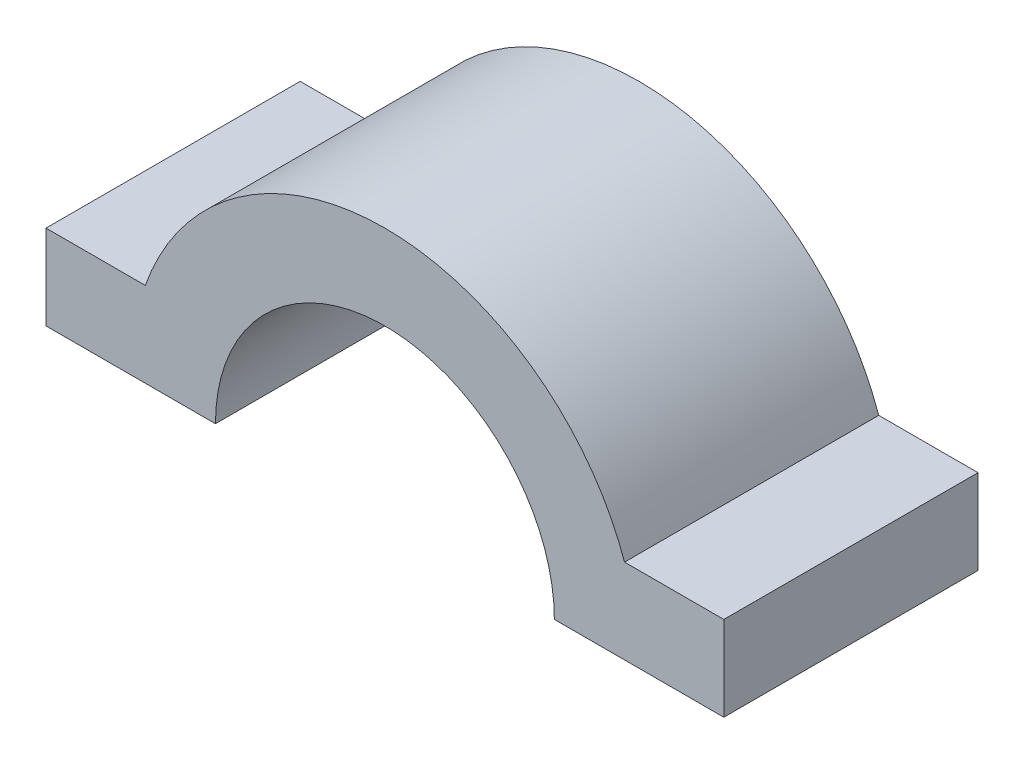
SolidWorks part; units mm, degrees
ref_plane "Alzado" through (0, 0, 0) normal (0, 0, 1) x (1, 0, 0)
ref_plane "Planta" through (0, 0, 0) normal (0, 1, 0) x (1, 0, 0)
ref_plane "Vista lateral" through (0, 0, 0) normal (1, 0, 0) x (0, 0, -1)
sketch "Croquis1" plane through (0, 0, 0) normal (0, 0, 1) x (1, 0, 0)
  line L0 (-10, 0) -> (10, 0) construction
  line L1 (10, 0) -> (20, 0)
  line L2 (-10, 0) -> (-20, 0)
  line L3 (-20, 0) -> (-20, 5)
  line L4 (-20, 5) -> (-14.1421, 5)
  line L5 (20, 0) -> (20, 5)
  line L6 (20, 5) -> (14.1421, 5)
  arc A1 (10, 0) -> (-10, 0) centre (0, 0) ccw
  arc A3 (-14.1421, 5) -> (14.1421, 5) centre (0, 0) cw
  point P4 (0, 0)
  dimension "D4" = 15
  dimension "D1" = 20
  dimension "D2" = 10
  dimension "D3" = 10
  dimension "D5" = 5
  dimension "D6" = 5
extrude "Saliente-Extruir1" add sketch "Croquis1" against normal blind 15
